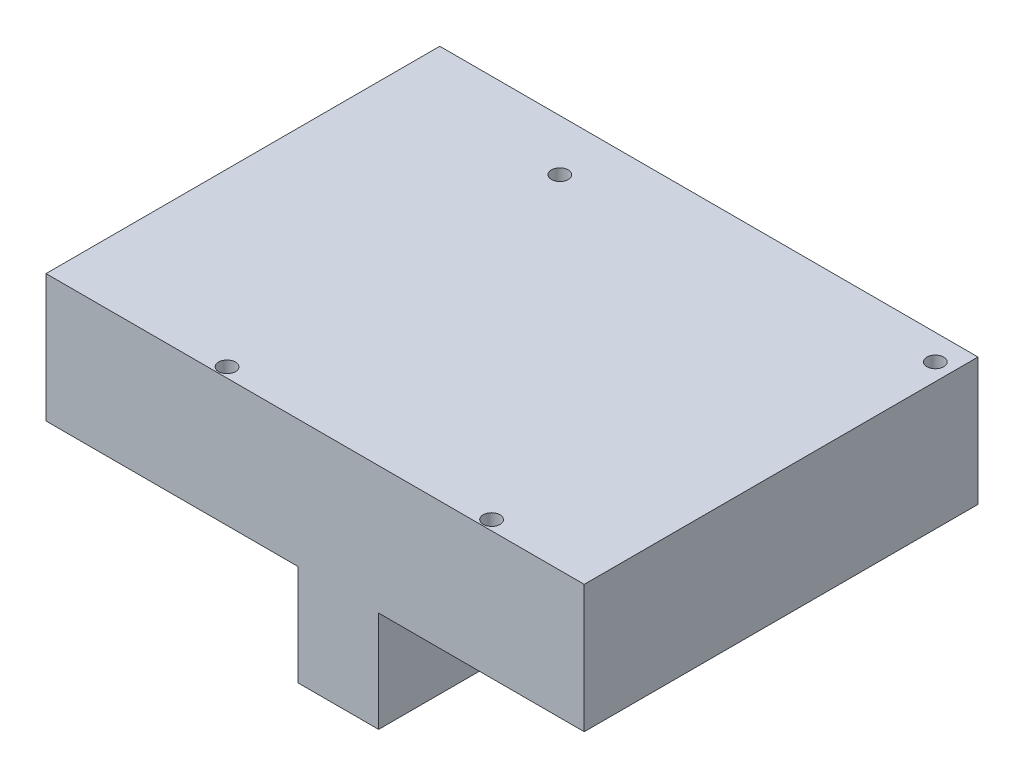
SolidWorks part; units mm, degrees
material "Epoxy, renforcé"
ref_plane "Plan de face" through (0, 0, 0) normal (0, 0, 1) x (1, 0, 0)
ref_plane "Plan de dessus" through (0, 0, 0) normal (0, 1, 0) x (1, 0, 0)
ref_plane "Plan de droite" through (0, 0, 0) normal (1, 0, 0) x (0, 0, -1)
sketch "Esquisse1" plane through (0, 0, 0) normal (0, 1, 0) x (1, 0, 0)
  line L1 (0, 0) -> (80.1, 0)
  line L2 (0, 0) -> (0, 58.6)
  line L3 (0, 58.6) -> (80.1, 58.6)
  line L4 (80.1, 0) -> (80.1, 58.6)
  dimension "D1" = 58.6
  dimension "D2" = 80.1
extrude "Boss.-Extru.1" add sketch "Esquisse1" along normal blind 19
sketch "Esquisse2" plane through (0, 0, 0) normal (0, -1, 0) x (1, 0, 0)
  line L0 (80.1, -58.6) -> (0, -58.6) construction
  line L1 (37.5, -58.6) -> (49.5, -58.6)
  line L2 (37.5, -58.6) -> (37.5, 0)
  line L3 (37.5, 0) -> (49.5, 0)
  line L4 (49.5, -58.6) -> (49.5, 0)
  line L5 (0, 0) -> (80.1, 0) construction
  line L6 (0, -58.6) -> (0, 0) construction
  point P10 (43.5, -58.6)
  dimension "D1" = 12
  dimension "D2" = 43.5
extrude "Boss.-Extru.2" add sketch "Esquisse2" along normal blind 15
sketch "Esquisse3" plane through (0, 19, 0) normal (0, 1, 0) x (1, 0, 0)
  line L0 (80.1, 58.6) -> (0, 58.6) construction
  line L2 (80.1, 0) -> (80.1, 58.6) construction
  circle A0 centre (77.56, 54.79) radius 1.25
  circle A1 centre (25.49, 50.98) radius 1.25
  circle A2 centre (25.49, 1.45) radius 1.25
  circle A3 centre (64.86, 1.45) radius 1.25
  dimension "D1" = 3.81
  dimension "D2" = 2.54
  dimension "D3" = 2.5
  dimension "D4" = 52.07
  dimension "D5" = 3.81
  dimension "D6" = 49.53
  dimension "D7" = 39.37
extrude "Enlèv. mat.-Extru.1" cut sketch "Esquisse3" against normal through all
